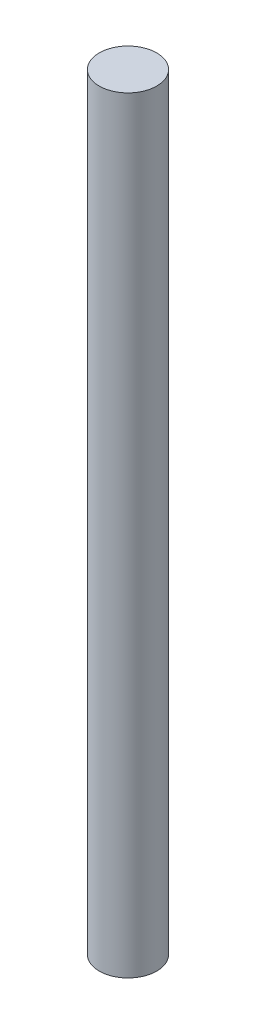
SolidWorks part; units mm, degrees
ref_plane "前视基准面" through (0, 0, 0) normal (0, 0, 1) x (1, 0, 0)
ref_plane "上视基准面" through (0, 0, 0) normal (0, 1, 0) x (1, 0, 0)
ref_plane "右视基准面" through (0, 0, 0) normal (1, 0, 0) x (0, 0, -1)
other "Configuration Table"
sketch "草图1" plane through (0, 0, 0) normal (0, 1, 0) x (1, 0, 0)
  circle A0 centre (0, 0) radius 0.75
  dimension "D1" = 1.5
extrude "凸台-拉伸1" add sketch "草图1" along normal blind 20
